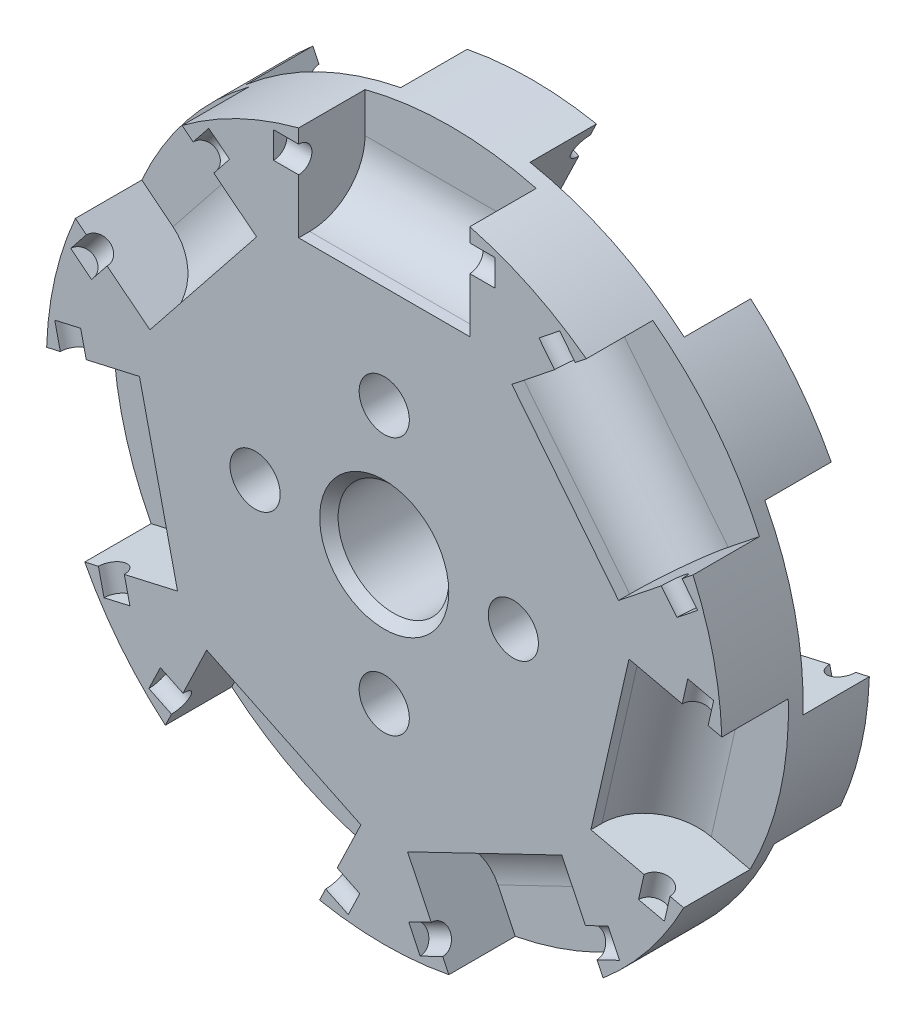
SolidWorks part; units mm, degrees
other "Markup1"
sketch "Sketch8" plane through (32.7336, 32.7336, 0) normal (0.5701, 0.1846, 0.8006) x (0.8043, 0.0736, -0.5897)
ref_plane "Front Plane" through (0, 0, 0) normal (0, 0, 1) x (1, 0, 0)
ref_plane "Top Plane" through (0, 0, 0) normal (0, 1, 0) x (1, 0, 0)
ref_plane "Right Plane" through (0, 0, 0) normal (1, 0, 0) x (0, 0, -1)
sketch "Sketch1" plane through (0, 0, 0) normal (0, 0, 1) x (1, 0, 0)
  circle A0 centre (0, 0) radius 29.0703
  dimension "D1" = 58.1406
extrude "Boss-Extrude2" add sketch "Sketch1" against normal blind 6.35
sketch "Sketch2" plane through (0, 0, 0) normal (0, 0, 1) x (1, 0, 0)
  line L1 (-12.7, 29.0703) -> (12.7, 29.0703) construction
  line L2 (-7.366, 30.3403) -> (7.366, 30.3403)
  line L3 (-7.366, 30.3403) -> (-7.366, 19.9263)
  line L4 (-7.366, 19.9263) -> (7.366, 19.9263)
  line L5 (7.366, 30.3403) -> (7.366, 19.9263)
  line L6 (-7.366, 30.3403) -> (7.366, 19.9263) construction
  line L7 (-7.366, 19.9263) -> (7.366, 30.3403) construction
  line L35 (0, 0) -> (0, 29.0703) construction
  circle A1 centre (0, 0) radius 29.0703 construction
  point P10 (0, 25.1333)
  circle M7 centre (0, 0) radius 29.0703
  dimension "D1" = 14.732
  dimension "D2" = 10.414
  dimension "D3" = 1.27
  dimension "D4" = 25.4
extrude "Cut-Extrude2" cut sketch "Sketch2" against normal blind 5.715 contours L5 L3 L4 M7
pattern_circular "CirPattern1" count 7 over 360 about axis through (0, 0, 0) along (0, 0, 1) of "Cut-Extrude2"
ref_plane "Plane1" through (0, 0, 0) normal (1, 0, 0) x (0, 0, -1)
sketch "Sketch4" plane through (0, 0, 0) normal (1, 0, 0) x (0, 0, -1)
  line L0 (5.715, 19.9263) -> (0, 19.9263) construction
  circle A0 centre (0, 25.7683) radius 1.143
  dimension "D1" = 2.286
  dimension "D2" = 5.842
extrude "Cut-Extrude4" cut sketch "Sketch4" against normal mid plane 19.05
pattern_circular "CirPattern2" count 7 over 360 about axis through (0, 0, 0) along (0, 0, 1) of "Cut-Extrude4"
sketch "Sketch5" plane through (0, 0, 0) normal (0, 0, 1) x (1, 0, 0)
  circle A0 centre (0, 0) radius 4.7625
  dimension "D1" = 9.525
extrude "Cut-Extrude5" cut sketch "Sketch5" against normal through all
sketch "Sketch6" plane through (0, 0, -6.35) normal (0, 0, -1) x (-1, 0, 0)
  circle A4 centre (0, 11.1125) radius 2.159
  circle A5 centre (11.1125, 0) radius 2.159
  circle A6 centre (0, -11.1125) radius 2.159
  circle A7 centre (-11.1125, 0) radius 2.159
  point P2 (0, 0)
  point P3 (2.4891, -10.8301)
  point P4 (0, 0)
  point P11 (0, 0)
  dimension "D3" = 4
  dimension "D2" = 4.318
  dimension "D1" = 11.1125
extrude "Cut-Extrude7" cut sketch "Sketch6" against normal through all
sketch "Sketch9" plane through (0, 0, -6.35) normal (0, 0, -1) x (-1, 0, 0)
  circle A0 centre (0, 0) radius 29.0703
  circle A5 centre (0, 11.1125) radius 2.159 construction
  circle A6 centre (0, 11.1125) radius 2.159
  circle A7 centre (11.1125, 0) radius 2.159
  circle A8 centre (0, -11.1125) radius 2.159
  circle A9 centre (0, 0) radius 29.0703 construction
  circle A10 centre (-11.1125, 0) radius 2.159
  circle A11 centre (0, 0) radius 4.7625 construction
  circle A12 centre (0, 0) radius 4.7625
  point P2 (0, 0)
  point P21 (0, 0)
  dimension "D1" = 4
extrude "Boss-Extrude3" add sketch "Sketch9" along normal blind 6.35
sketch "Sketch10" plane through (0, 0, -12.7) normal (0, 0, -1) x (-1, 0, 0)
  line L0 (-25.313, 26.1915) -> (0.087, 26.1915) construction
  line L1 (-2.0091, 21.149) -> (-15.2822, 14.7571)
  line L2 (-2.0091, 21.149) -> (-6.5275, 30.5317)
  line L3 (-6.5275, 30.5317) -> (-19.8006, 24.1398)
  line L4 (-15.2822, 14.7571) -> (-19.8006, 24.1398)
  line L5 (-2.0091, 21.149) -> (-19.8006, 24.1398) construction
  line L6 (-6.5275, 30.5317) -> (-15.2822, 14.7571) construction
  line L7 (0, 0) -> (-12.613, 26.1915) construction
  line L8 (0, 0) -> (0, 40.3277) construction
  circle A2 centre (0, 0) radius 29.0703 construction
  point P8 (-10.9048, 22.6444)
  dimension "D1" = 1.27
  dimension "D2" = 14.732
  dimension "D3" = 10.414
  dimension "D4" = 25.4
  dimension "D5" = 25.714
extrude "Cut-Extrude8" cut sketch "Sketch10" against normal blind 5.715
pattern_circular "CirPattern3" count 7 over 360 about axis through (0, 0, 0) along (0, 0, 1) of "Cut-Extrude8"
ref_plane "Plane2" through (0, 0, 0) normal (-0.901, 0.4339, 0) x (0, 0, -1)
sketch "Sketch11" plane through (0, 0, 0) normal (-0.901, 0.4339, 0) x (0, 0, -1)
  line L5 (6.985, -19.9263) -> (12.7, -19.9263) construction
  line L6 (12.7, -28.1216) -> (12.7, -23.2925) construction
  circle A0 centre (12.7, -25.7683) radius 1.143
  dimension "D1" = 2.286
  dimension "D2" = 5.842
extrude "Cut-Extrude9" cut sketch "Sketch11" against normal mid plane 19.05
pattern_circular "CirPattern4" count 7 over 360 about axis through (0, 0, 0) along (0, 0, 1) of "Cut-Extrude9"
fillet "Fillet1" radius 4.7625 14 edges at (-15.579, 12.4238, -5.715) (0, 19.9263, -5.715) (8.6456, 17.953, -6.985) (-8.6458, 17.9529, -6.985) (-19.4267, 4.4339, -6.985) (-15.5789, -12.4239, -6.985) (0.0001, -19.9263, -6.985) (15.5791, -12.4238, -6.985) (19.4267, 4.4341, -6.985) (8.6457, -17.953, -5.715) (19.4267, -4.434, -5.715) (-19.4267, -4.434, -5.715) (-8.6457, -17.953, -5.715) (15.579, 12.4238, -5.715)
chamfer "Chamfer1" distance 0.7937 angle 45 2 edges at (-4.7625, 0, -12.7) (4.7625, 0, 0)
